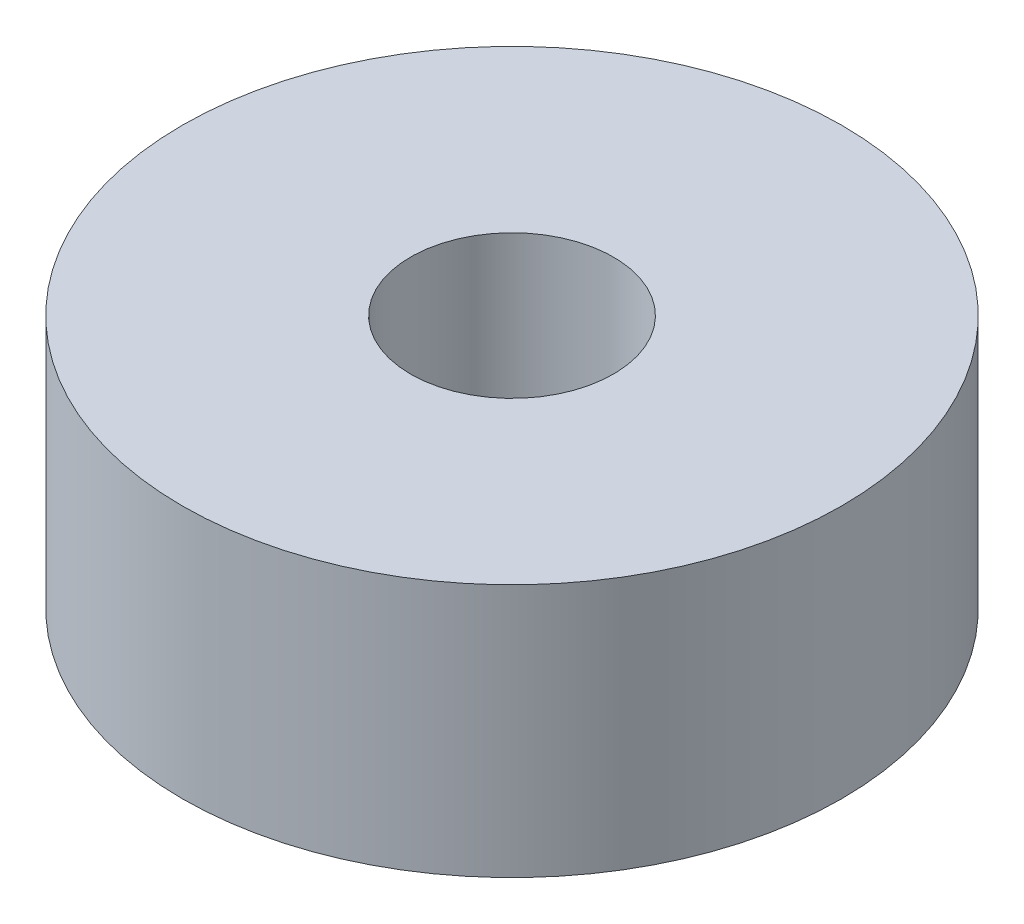
SolidWorks part; units mm, degrees
ref_plane "Alzado" through (0, 0, 0) normal (0, 0, 1) x (1, 0, 0)
ref_plane "Planta" through (0, 0, 0) normal (0, 1, 0) x (1, 0, 0)
ref_plane "Vista lateral" through (0, 0, 0) normal (1, 0, 0) x (0, 0, -1)
sketch "Croquis1" plane through (0, 0, 0) normal (0, 1, 0) x (1, 0, 0)
  circle A0 centre (0, 0) radius 6.5
  circle A1 centre (0, 0) radius 2
  dimension "D1" = 13
  dimension "D2" = 4
extrude "Saliente-Extruir1" add sketch "Croquis1" along normal blind 5
